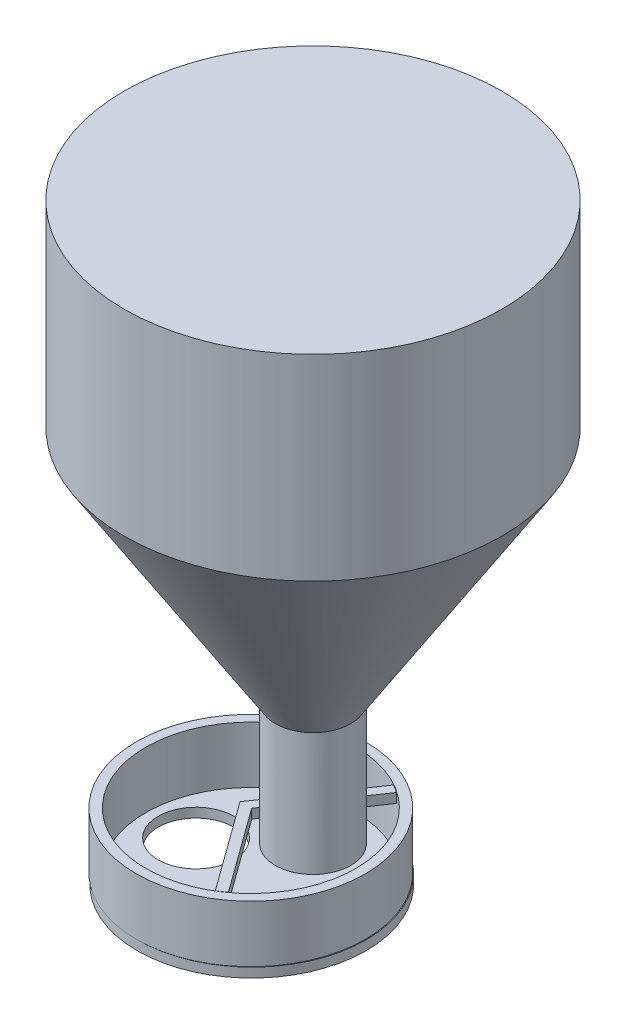
SolidWorks part; units mm, degrees
ref_plane "Alzado" through (0, 0, 0) normal (0, 0, 1) x (1, 0, 0)
ref_plane "Planta" through (0, 0, 0) normal (0, 1, 0) x (1, 0, 0)
ref_plane "Vista lateral" through (0, 0, 0) normal (1, 0, 0) x (0, 0, -1)
sketch "Croquis1" plane through (0, 0, 0) normal (0, 1, 0) x (1, 0, 0)
  circle A0 centre (0, 0) radius 100
  dimension "D1" = 200
ref_plane "Plano1" through (0, -230, 0) normal (0, 1, 0) x (1, 0, 0)
extrude "Saliente-Extruir1" add sketch "Croquis1" against normal blind 104 contours A0
sketch "Croquis2" plane through (0, -104, 0) normal (0, -1, 0) x (1, 0, 0)
  circle A2 centre (0, 0) radius 100
sketch "Croquis3" plane through (0, -230, 0) normal (0, 1, 0) x (1, 0, 0)
  circle A0 centre (0, 0) radius 20
  dimension "D1" = 40
loft "Recubrir1" add profiles "Croquis3", "Croquis2"
sketch "Croquis4" plane through (0, -230, 0) normal (0, -1, 0) x (1, 0, 0)
  circle A0 centre (0, 0) radius 20
  dimension "D1" = 40
extrude "Saliente-Extruir2" add sketch "Croquis4" along normal blind 65
ref_plane "Plano2" through (0, 0, -20) normal (0, 0, -1) x (-1, 0, 0)
sketch "Croquis7" plane through (0, -295, 0) normal (0, -1, 0) x (1, 0, 0)
  circle A0 centre (0, 0) radius 17.5
  dimension "D1" = 35
extrude "Cortar-Extruir2" cut sketch "Croquis7" against normal blind 24
sketch "Croquis8" plane through (0, -295, 0) normal (0, -1, 0) x (1, 0, 0)
  circle A0 centre (-32.8935, 0) radius 60.6028
  circle A1 centre (-32.8935, 0) radius 55.6028
  dimension "D1" = 5
extrude "Saliente-Extruir3" add sketch "Croquis8" along normal blind 30 separate body
sketch "Croquis9" plane through (0, -295, 0) normal (0, 1, 0) x (1, 0, 0)
  circle A0 centre (-32.4436, 0) radius 60.6028
sketch "Croquis10" plane through (0, -325, 0) normal (0, -1, 0) x (1, 0, 0)
  circle A0 centre (-32.4436, 0) radius 60.6028
  circle A1 centre (-63.5378, -1.6179) radius 20
  dimension "D1" = 40
extrude "Saliente-Extruir5" add sketch "Croquis10" along normal blind 5
sketch "Croquis11" plane through (0, -295, 0) normal (0, 1, 0) x (1, 0, 0)
  line L0 (-0.1084, -44.6798) -> (-32.4436, 0)
  line L1 (-32.4436, 0) -> (-1.3577, 45.5578)
  line L2 (-4.2921, -47.4272) -> (-38.5544, -0.0846)
  line L3 (-38.5544, -0.0846) -> (-5.6158, 48.1884)
  line L4 (-4.0505, -47.761) -> (-38.5544, -0.0846) construction
  line L5 (0, -44.8296) -> (-32.4436, 0) construction
  line L6 (-32.4436, 0) -> (-1.2478, 45.719) construction
  line L7 (-38.5544, -0.0846) -> (-5.3779, 48.5371) construction
  arc A2 (-1.3577, 45.5578) -> (-5.6158, 48.1884) centre (-32.4436, 0) ccw
  arc A3 (-4.2921, -47.4272) -> (-0.1084, -44.6798) centre (-32.4436, 0) ccw
  dimension "D1" = 5
extrude "Saliente-Extruir6" add sketch "Croquis11" against normal blind 5 separate body
